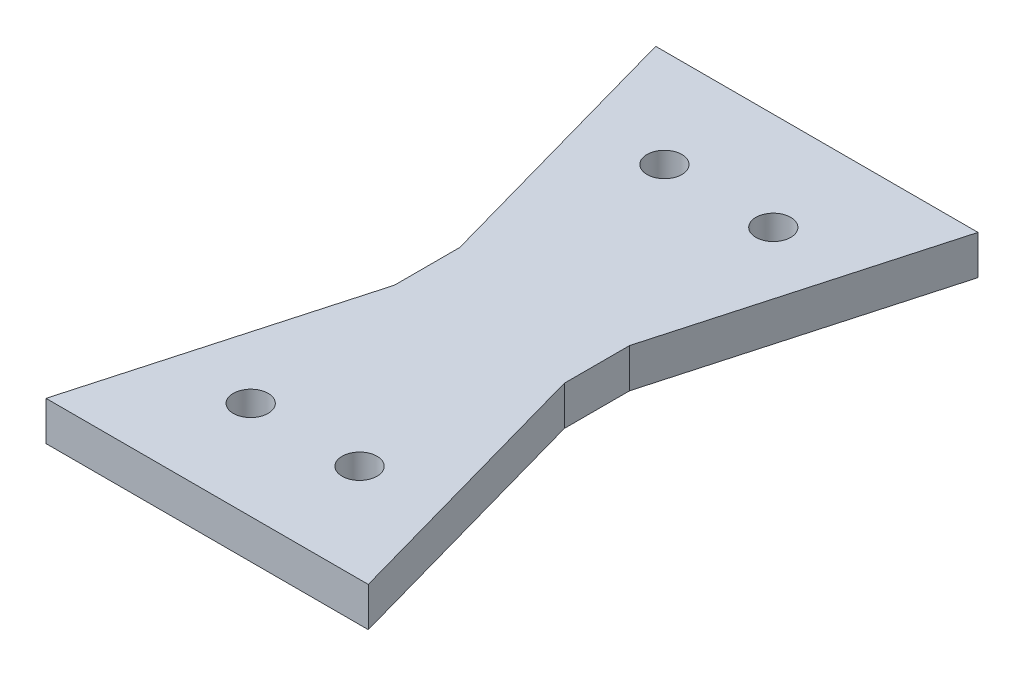
SolidWorks part; units mm, degrees
ref_plane "Front Plane" through (0, 0, 0) normal (0, 0, 1) x (1, 0, 0)
ref_plane "Top Plane" through (0, 0, 0) normal (0, 1, 0) x (1, 0, 0)
ref_plane "Right Plane" through (0, 0, 0) normal (1, 0, 0) x (0, 0, -1)
sketch "Sketch1" plane through (0, 0, 0) normal (0, 1, 0) x (1, 0, 0)
  line L0 (0, 73.2507) -> (0, -64.7074) construction
  line L1 (75.9403, 0) -> (-146.5014, 0) construction
  line L3 (-37, 70) -> (-30, 45)
  line L4 (-37, 70) -> (37, 70)
  line L7 (-30, 45) -> (-19.5, 7.5)
  line L8 (-19.5, 7.5) -> (-19.5, -7.5)
  line L9 (19.5, 7.5) -> (19.5, -7.5)
  line L10 (30, 45) -> (19.5, 7.5)
  line L11 (37, 70) -> (30, 45)
  line L12 (37, -70) -> (30, -45)
  line L13 (30, -45) -> (19.5, -7.5)
  line L14 (-30, -45) -> (-19.5, -7.5)
  line L15 (-37, -70) -> (37, -70)
  line L16 (-37, -70) -> (-30, -45)
  circle A0 centre (-12.5, 47.5) radius 4
  circle A1 centre (12.5, 47.5) radius 4
  circle A2 centre (12.5, -47.5) radius 4
  circle A3 centre (-12.5, -47.5) radius 4
  point P14 (0, 70)
  point P21 (0, 70)
  point P28 (19.5, 0)
  point P29 (-19.5, 0)
  point P31 (0, -70)
  dimension "D5" = 8
  dimension "D6" = 12.5
  dimension "D7" = 22.5
  dimension "D1" = 37
  dimension "D2" = 70
  dimension "D3" = 30
  dimension "D4" = 25
  dimension "D8" = 62.5
  dimension "D9" = 19.5
extrude "Boss-Extrude1" add sketch "Sketch1" along normal blind 9
